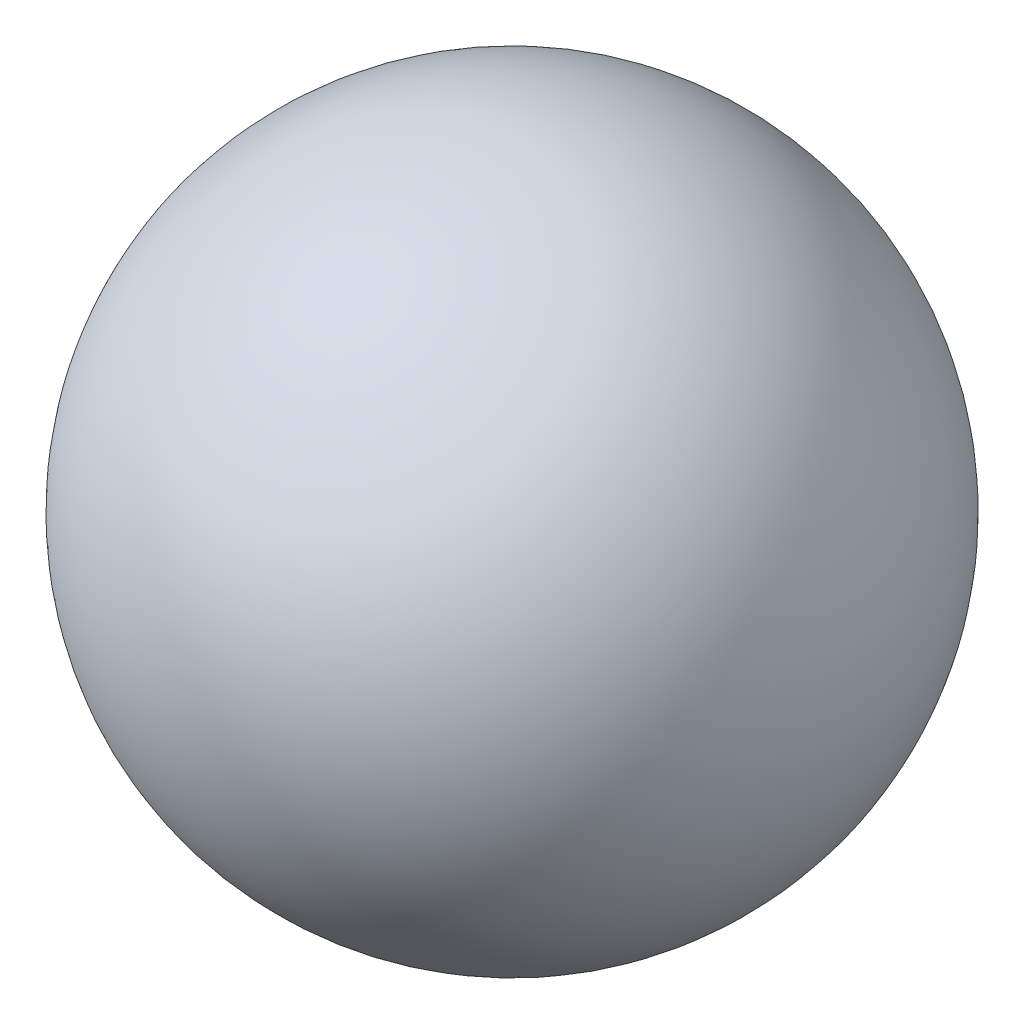
SolidWorks part; units mm, degrees
ref_plane "Plan1" through (0, 0, 0) normal (0, 0, 1) x (1, 0, 0)
ref_plane "Plan2" through (0, 0, 0) normal (0, 1, 0) x (1, 0, 0)
ref_plane "Plan3" through (0, 0, 0) normal (1, 0, 0) x (0, 0, -1)
sketch "Esquisse1" plane through (0, 0, 0) normal (0, 0, 1) x (1, 0, 0)
  line L0 (4.8879, 11.75) -> (-5.0679, 11.75) construction
  line L1 (-2.4286, 11.75) -> (2.4286, 11.75)
  arc A0 (2.4286, 11.75) -> (-2.4286, 11.75) centre (0, 11.75) ccw
  dimension "D1" = 2.4286
revolve "Base-Révolution" add sketch "Esquisse1" angle 360 about L0
